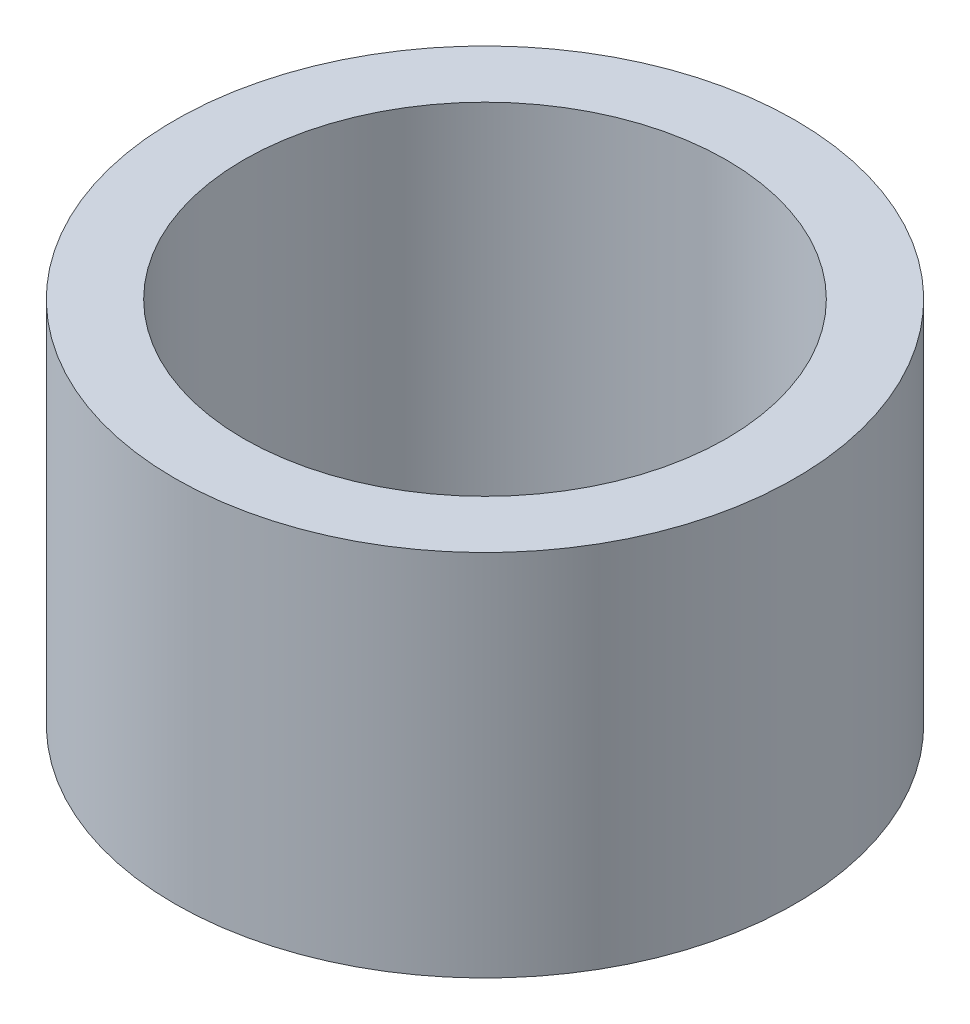
SolidWorks part; units mm, degrees
ref_plane "Front Plane" through (0, 0, 0) normal (0, 0, 1) x (1, 0, 0)
ref_plane "Top Plane" through (0, 0, 0) normal (0, 1, 0) x (1, 0, 0)
ref_plane "Right Plane" through (0, 0, 0) normal (1, 0, 0) x (0, 0, -1)
sketch "Sketch1" plane through (0, 0, 0) normal (0, 1, 0) x (1, 0, 0)
  circle A0 centre (0, 0) radius 4.1999
  circle A1 centre (0, 0) radius 5.3975
  dimension "D1" = 8.3998
  dimension "D2" = 10.795
extrude "Boss-Extrude1" add sketch "Sketch1" along normal blind 6.4115
